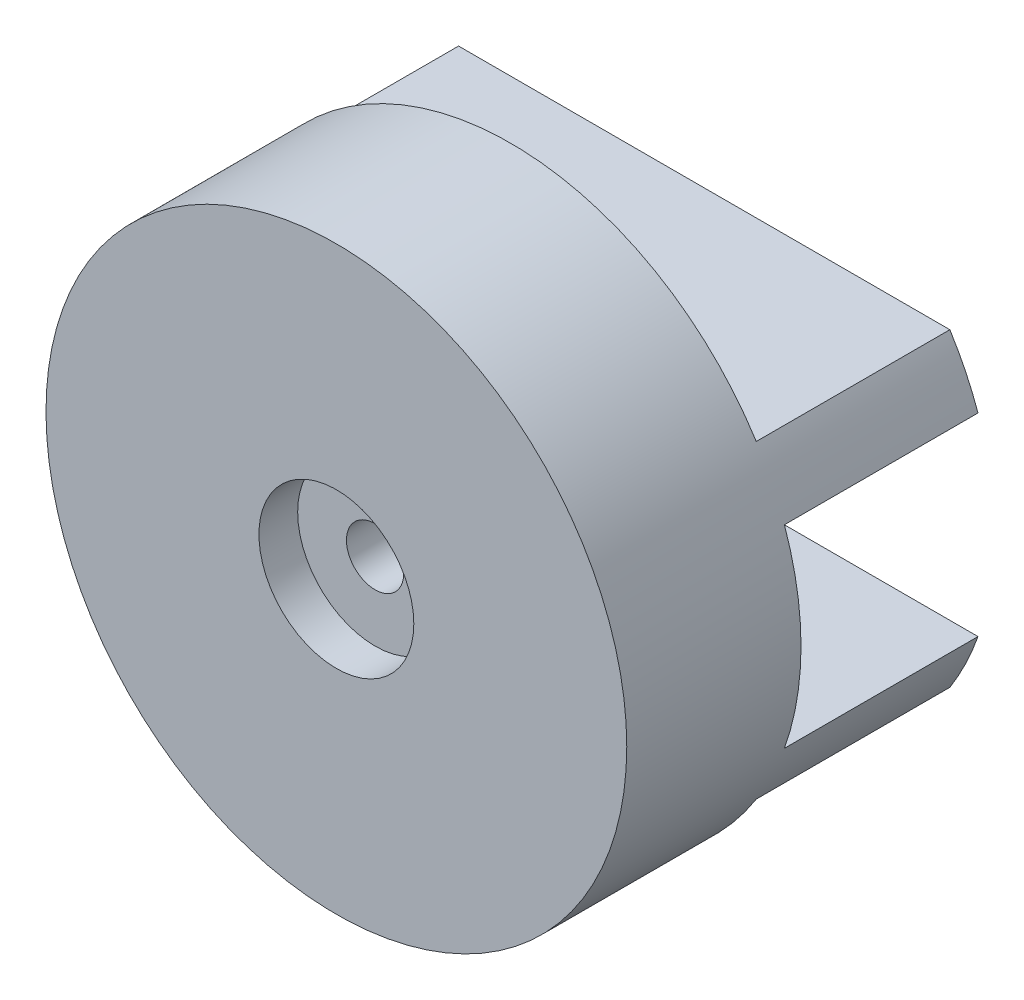
SolidWorks part; units mm, degrees
ref_plane "Alzado" through (0, 0, 0) normal (0, 0, 1) x (1, 0, 0)
ref_plane "Planta" through (0, 0, 0) normal (0, 1, 0) x (1, 0, 0)
ref_plane "Vista lateral" through (0, 0, 0) normal (1, 0, 0) x (0, 0, -1)
sketch "Croquis1" plane through (0, 0, 0) normal (0, 0, 1) x (1, 0, 0)
  circle A0 centre (0, 0) radius 75
extrude "Saliente-Extruir1" add sketch "Croquis1" along normal blind 15
sketch "Croquis2" plane through (0, 0, 0) normal (0, 0, -1) x (-1, 0, 0)
  line L0 (0, 0) -> (0, 25)
  line L1 (0, 0) -> (0, -25)
  line L2 (-70.7107, -25) -> (70.7107, -25)
  line L3 (0, 25) -> (-70.7107, 25)
  line L4 (-70.7107, 25) -> (70.7107, 25)
  line L5 (0, 25) -> (0, 40)
  line L6 (-63.4429, 40) -> (63.4429, 40)
  line L7 (0, 0) -> (-13.3847, 0)
  line L8 (-63.4429, -40) -> (63.4429, -40)
  line L9 (0, -25) -> (0, -40)
  line L10 (-70.7107, -25) -> (70.7107, -25)
  line L11 (0, -25) -> (-70.7107, -25)
  circle A0 centre (0, 0) radius 75 construction
  arc A1 (-63.4429, 40) -> (-70.7107, 25) centre (0, 0) ccw
  arc A2 (63.4429, 40) -> (70.7107, 25) centre (0, 0) cw
  arc A3 (63.4429, -40) -> (70.7107, -25) centre (0, 0) ccw
  arc A4 (-63.4429, -40) -> (-70.7107, -25) centre (0, 0) cw
  circle M9 centre (0, 0) radius 75
extrude "Saliente-Extruir2" add sketch "Croquis2" along normal blind 60 contours L6 L3 L5 M9 | L6 L5 L4 M9 | L2 L9 L8 M9 | L9 L2 L8 M9
sketch "Croquis3" plane through (0, 0, 15) normal (0, 0, 1) x (1, 0, 0)
  circle A0 centre (0, 0) radius 60
  circle A1 centre (0, 0) radius 75
extrude "Saliente-Extruir3" add sketch "Croquis3" along normal blind 20
sketch "Croquis4" plane through (0, 0, 15) normal (0, 0, 1) x (1, 0, 0)
  circle A0 centre (0, 0) radius 25
extrude "Cortar-Extruir1" cut sketch "Croquis4" against normal blind 20
sketch "Croquis5" plane through (0, 0, 35) normal (0, 0, 1) x (1, 0, 0)
  circle A0 centre (0, 0) radius 30
  circle A1 centre (0, 0) radius 60
extrude "Saliente-Extruir4" add sketch "Croquis5" against normal blind 30
sketch "Croquis6" plane through (0, 0, 15) normal (0, 0, 1) x (1, 0, 0)
  circle A0 centre (0, 0) radius 30
  circle A1 centre (0, 0) radius 25
extrude "Saliente-Extruir5" add sketch "Croquis6" along normal blind 10
sketch "Croquis7" plane through (0, 0, 35) normal (0, 0, 1) x (1, 0, 0)
  circle A0 centre (0, 0) radius 30
  circle A1 centre (0, 0) radius 20
extrude "Saliente-Extruir6" add sketch "Croquis7" against normal up to surface (35 mm away) contours A0 | A1 up to face at (-42.6777, 0, 0)
sketch "Croquis8" plane through (0, 0, 0) normal (0, 0, -1) x (-1, 0, 0)
  circle A0 centre (0, 0) radius 7.4
  circle A1 centre (0, 0) radius 20
extrude "Saliente-Extruir7" add sketch "Croquis8" against normal blind 25
sketch "Croquis9" plane through (0, 0, 0) normal (0, 0, -1) x (-1, 0, 0)
  line L0 (-63.4429, 40) -> (63.4429, 40)
  line L1 (-70.7107, 25) -> (70.7107, 25)
  line L2 (-70.7107, -25) -> (70.7107, -25)
  line L3 (-63.4429, -40) -> (63.4429, -40)
  arc A1 (-63.4429, 40) -> (63.4429, 40) centre (0, 0) cw
  arc A2 (-63.4429, -40) -> (63.4429, -40) centre (0, 0) ccw
  arc A3 (-70.7107, 25) -> (-70.7107, -25) centre (0, 0) ccw
  arc A4 (70.7107, 25) -> (70.7107, -25) centre (0, 0) cw
  circle A5 centre (0, 0) radius 7.4
extrude "Saliente-Extruir9" add sketch "Croquis9" along normal blind 10
